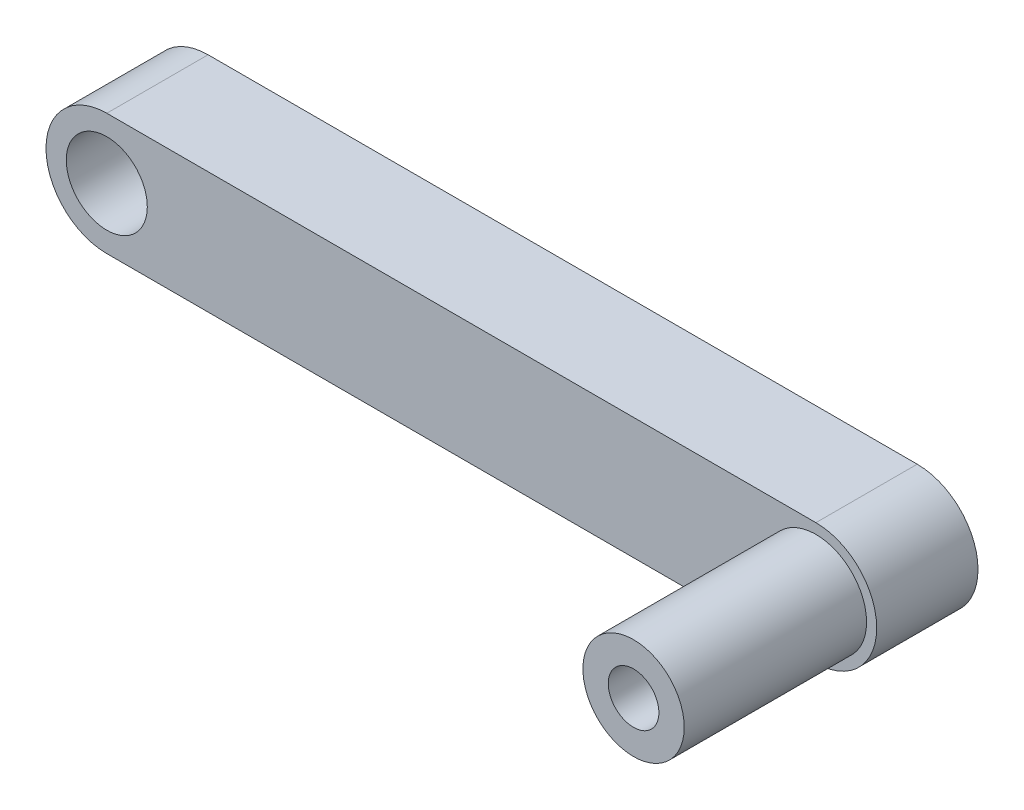
SolidWorks part; units mm, degrees
ref_plane "Plan de face" through (0, 0, 0) normal (0, 0, 1) x (1, 0, 0)
ref_plane "Plan de dessus" through (0, 0, 0) normal (0, 1, 0) x (1, 0, 0)
ref_plane "Plan de droite" through (0, 0, 0) normal (1, 0, 0) x (0, 0, -1)
sketch "Croquis1" plane through (0, 0, 0) normal (0, 0, 1) x (1, 0, 0)
  line L0 (60.2674, 6) -> (-9.7326, 6)
  line L1 (60.2674, -6) -> (-9.7326, -6)
  arc A0 (60.2674, -6) -> (60.2674, 6) centre (60.2674, 0) ccw
  arc A2 (-9.7326, 6) -> (-9.7326, -6) centre (-9.7326, 0) ccw
  circle A3 centre (-9.7326, 0) radius 4
  dimension "D2" = 12
  dimension "D3" = 70
  dimension "D1" = 8
extrude "Saliente-Extruir1" add sketch "Croquis1" along normal blind 10
sketch "Croquis2" plane through (0, 0, 10) normal (0, 0, 1) x (1, 0, 0)
  circle A1 centre (60.2674, 0) radius 5
  circle A2 centre (60.2674, 0) radius 2.5
  dimension "D1" = 10
  dimension "D2" = 5
extrude "Saliente-Extruir2" add sketch "Croquis2" along normal blind 18
